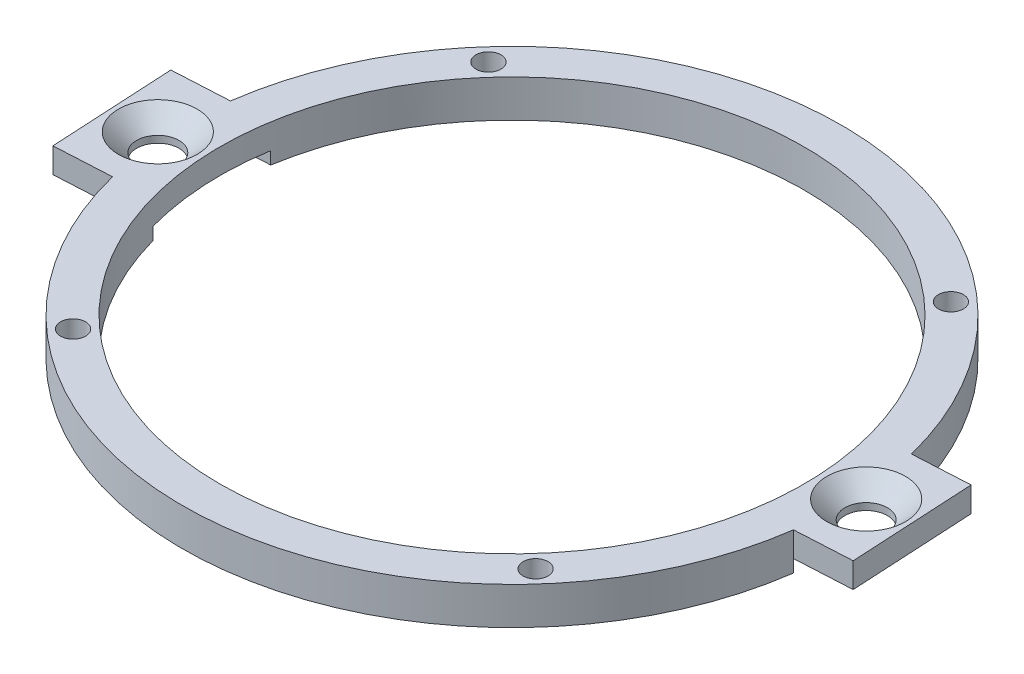
SolidWorks part; units mm, degrees
ref_plane "Front Plane" through (0, 0, 0) normal (0, 0, 1) x (1, 0, 0)
ref_plane "Top Plane" through (0, 0, 0) normal (0, 1, 0) x (1, 0, 0)
ref_plane "Right Plane" through (0, 0, 0) normal (1, 0, 0) x (0, 0, -1)
sketch "Sketch1" plane through (0, 0, 0) normal (0, 1, 0) x (1, 0, 0)
  line L0 (-103.942, -29.8585) -> (-100.42, -29.6693)
  line L1 (-43.0937, -26.5892) -> (-42.5572, -36.5748)
  line L2 (-42.5572, -36.5748) -> (-46.0792, -36.764)
  line L3 (-103.4055, -39.8441) -> (-103.942, -29.8585)
  line L4 (-46.6157, -26.7784) -> (-43.0937, -26.5892)
  line L5 (-99.8835, -39.6549) -> (-103.4055, -39.8441)
  line L6 (-100.42, -29.6693) -> (-99.4037, -29.6147)
  line L7 (-99.8835, -39.6549) -> (-98.8672, -39.6003)
  line L9 (-47.632, -26.833) -> (-46.6157, -26.7784)
  line L10 (-47.0955, -36.8186) -> (-46.0792, -36.764)
  circle A0 centre (-73.2496, -33.2167) radius 23.401
  arc A1 (-98.8672, -39.6003) -> (-47.0955, -36.8186) centre (-73.2496, -33.2167) ccw
  circle A2 centre (-73.2496, -33.2167) radius 26.401 construction
  arc A3 (-47.632, -26.833) -> (-99.4037, -29.6147) centre (-73.2496, -33.2167) ccw
  dimension "D1" = 3
extrude "Boss-Extrude1" add sketch "Sketch1" along normal blind 2
sketch "Sketch2" plane through (0, 2, 0) normal (0, 1, 0) x (1, 0, 0)
  line L0 (-103.6737, -34.8513) -> (-42.8255, -31.582) construction
  line L1 (-103.942, -29.8585) -> (-103.4055, -39.8441) construction
  line L2 (-42.5572, -36.5748) -> (-43.0937, -26.5892) construction
  line L3 (-73.2496, -33.2167) -> (-52.8924, -10.5477) construction
  line L4 (-73.2496, -33.2167) -> (-74.8843, -2.7925) construction
  line L5 (-73.2496, -33.2167) -> (-95.9186, -12.8594) construction
  line L6 (-73.2496, -33.2167) -> (-93.6068, -55.8856) construction
  line L7 (-73.2496, -33.2167) -> (-50.5806, -53.5739) construction
  circle A0 centre (-91.7766, -16.579) radius 1
  circle A1 centre (-56.612, -14.6897) radius 1
  circle A2 centre (-54.7226, -49.8543) radius 1
  circle A3 centre (-89.8872, -51.7436) radius 1
  dimension "D1" = 4
extrude "Cut-Extrude1" cut sketch "Sketch2" against normal blind 10
sketch "Sketch5" plane through (0, 2, 0) normal (0, 1, 0) x (1, 0, 0)
  circle A0 centre (-100.1788, -34.6635) radius 2.8
  circle A1 centre (-46.3204, -31.7698) radius 2.8
sketch "Sketch6" plane through (0, 0, 0) normal (0, -1, 0) x (1, 0, 0)
  line L0 (-98.8672, 39.6003) -> (-95.809, 39.436)
  line L2 (-99.4037, 29.6147) -> (-96.3455, 29.4504)
  line L4 (-42.5572, 36.5748) -> (-42.6359, 36.4719)
  line L5 (-50.1537, 36.9829) -> (-47.0955, 36.8186)
  line L6 (-50.6902, 26.9973) -> (-47.632, 26.833)
  arc A0 (-50.1537, 36.9829) -> (-95.809, 39.436) centre (-73.2496, 33.2167) ccw
  arc A2 (-96.3455, 29.4504) -> (-50.6902, 26.9973) centre (-73.2496, 33.2167) ccw
  arc A3 (-99.4037, 29.6147) -> (-47.632, 26.833) centre (-73.2496, 33.2167) ccw
  circle A4 centre (-89.8872, 51.7436) radius 1
  circle A5 centre (-54.7226, 49.8543) radius 1
  circle A6 centre (-91.7766, 16.579) radius 1
  circle A7 centre (-56.612, 14.6897) radius 1
  arc A8 (-47.0955, 36.8186) -> (-98.8672, 39.6003) centre (-73.2496, 33.2167) ccw
  circle M3 centre (-89.8872, 51.7436) radius 1
  circle M4 centre (-54.7226, 49.8543) radius 1
  circle M5 centre (-56.612, 14.6897) radius 1
  circle M6 centre (-91.7766, 16.579) radius 1
  arc M7 (-99.4037, 29.6147) -> (-47.632, 26.833) centre (-73.2496, 33.2167) ccw
  arc M11 (-47.0955, 36.8186) -> (-98.8672, 39.6003) centre (-73.2496, 33.2167) ccw
  circle M15 centre (-73.2496, 33.2167) radius 23.401
extrude "Boss-Extrude3" add sketch "Sketch6" along normal blind 1 contours L5 L0 M15 M11 M3 M4 | L6 L2 M15 M7 M6 M5
hole_wizard "CSK for M3 Flat Head Machine Screw1" positions "3DSketch1" profile "Sketch9" countersink size "M3" standard "Ansi Metric" end condition through all
sketch3d "3DSketch1"
  point P0 (-100.1788, 2, 34.6635)
  point P3 (-46.3204, 2, 31.7698)
sketch "Sketch9" plane through (-100.1788, 2, 34.6635) normal (1, 0, 0) x (0, 0, 1)
  line L0 (0, 0) -> (0, 3)
  line L1 (0, 3) -> (1.7, 3)
  line L2 (1.7, 3) -> (1.7, 1.45)
  line L3 (1.7, 1.45) -> (3.15, 0)
  line L5 (3.15, 0) -> (0, 0)
  line L6 (-1.7, 1.45) -> (-3.15, 0) construction
  line L11 (0, -6.35) -> (0, 107.95) construction
  dimension "Thru Hole Dia." = 3.4
  dimension "Thru Hole Depth" = 3
  dimension "Near C'Sink Dia." = 6.3
  dimension "Near C'Sink Angle" = 90
sketch "Sketch10" plane through (0, 2, 0) normal (0, 1, 0) x (1, 0, 0)
  line L0 (-103.6737, -34.8513) -> (-42.8255, -31.582) construction
  line L1 (-103.942, -29.8585) -> (-103.4055, -39.8441) construction
  line L2 (-42.5572, -36.5748) -> (-43.0937, -26.5892) construction
sketch "Sketch11" plane through (0, 0, 0) normal (0, -1, 0) x (1, 0, 0)
  line L0 (-103.6737, 34.8513) -> (-42.8255, 31.582) construction
  line L1 (-103.942, 29.8585) -> (-103.4055, 39.8441) construction
ref_plane "Plane1" through (1.5687, 0, 29.1967) normal (0.0537, 0, 0.9986) x (0.9986, 0, -0.0537)
sketch "Sketch12" plane through (0, 2, 0) normal (0, 1, 0) x (1, 0, 0)
  line L0 (-74.6661, -6.8537) -> (-71.8331, -59.5796) construction
  arc A0 (-47.632, -26.833) -> (-99.4037, -29.6147) centre (-73.2496, -33.2167) ccw construction
  arc A1 (-98.8672, -39.6003) -> (-47.0955, -36.8186) centre (-73.2496, -33.2167) ccw construction
sketch "Sketch14" plane through (0, -1, 0) normal (0, -1, 0) x (1, 0, 0)
  line L0 (-71.8331, 59.5796) -> (-74.6661, 6.8537) construction
  arc A0 (-47.0955, 36.8186) -> (-98.8672, 39.6003) centre (-73.2496, 33.2167) ccw construction
ref_plane "Plane2" through (-74.8183, 0, 4.02) normal (0.9986, 0, -0.0537) x (-0.0537, 0, -0.9986)
sketch "Sketch16" plane through (0, -1, 0) normal (0, -1, 0) x (1, 0, 0)
  point P3 (-89.8872, 51.7436)
  point P4 (-54.7226, 49.8543)
  point P7 (-56.612, 14.6897)
  point P9 (-91.7766, 16.579)
